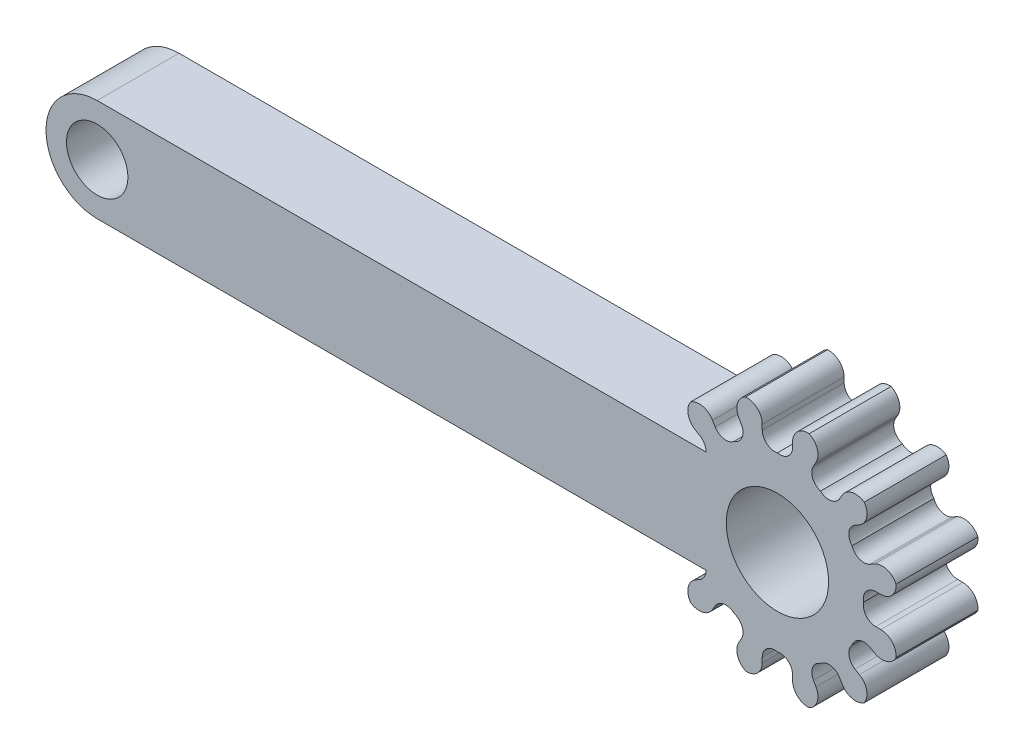
SolidWorks part; units mm, degrees
ref_plane "Front Plane" through (0, 0, 0) normal (0, 0, 1) x (1, 0, 0)
ref_plane "Top Plane" through (0, 0, 0) normal (0, 1, 0) x (1, 0, 0)
ref_plane "Right Plane" through (0, 0, 0) normal (1, 0, 0) x (0, 0, -1)
sketch "Sketch1" plane through (0, 0, 0) normal (0, 0, 1) x (1, 0, 0)
  line L0 (-18, 0) -> (15.2239, 0) construction
  line L1 (-18, 0) -> (-18, 2.5) construction
  line L2 (-18, 2.5) -> (9.7696, 2.5)
  line L3 (-18, -2.5) -> (9.7696, -2.5)
  arc A0 (-18, 2.5) -> (-18, -2.5) centre (-18, 0) ccw
  circle A1 centre (-18, 0) radius 1.5
  arc A3 (9.7696, -2.5) -> (9.7696, 2.5) centre (15.2239, 0) ccw
  point P4 (0, 0)
  dimension "D2" = 3
  dimension "D3" = 5
  dimension "D1" = 12
extrude "Boss-Extrude1" add sketch "Sketch1" along normal blind 4
sketch "Sketch2" plane through (0, 0, 4) normal (0, 0, 1) x (1, 0, 0)
  line L0 (15.2239, 0) -> (15.2239, -8.1619) construction
  line L1 (15.2239, -8.1619) -> (15.2239, 0) construction
  line L2 (15.2239, 6) -> (15.2239, -8.1619) construction
  line L3 (15.2239, 0) -> (19.4666, 4.2426) construction
  line L4 (15.2239, 0) -> (16.7769, 5.7956) construction
  line L5 (15.2239, 0) -> (17.3289, 3.646) construction
  line L6 (17.1076, 4.7464) -> (16.9838, 4.5292)
  line L7 (18.3927, 4.0045) -> (18.2664, 3.7887)
  arc A1 (16.7769, 5.7956) -> (17.1076, 4.7464) centre (16.4559, 5.1177) cw
  arc A6 (9.7696, -2.5) -> (9.7696, 2.5) centre (15.2239, 0) ccw construction
  arc A7 (16.9838, 4.5292) -> (17.3289, 3.646) centre (17.5138, 4.2273) ccw
  arc A8 (18.2664, 3.7887) -> (17.3289, 3.646) centre (17.7399, 4.0967) cw
  arc A9 (19.4666, 4.2426) -> (18.3927, 4.0045) centre (19.04, 3.6258) ccw
  arc A10 (16.7769, 5.7956) -> (19.4666, 4.2426) centre (17.517, 3.9717) cw
  dimension "D6" = 1.1
  dimension "D5" = 0.75
  dimension "D8" = 0.61
  dimension "D1" = 15
  dimension "D2" = 30
  dimension "D3" = 4.21
  dimension "D4" = 15
  dimension "D7" = 0.25
extrude "Cut-Extrude1" cut sketch "Sketch2" against normal through all
pattern_circular "CirPattern1" count 12 over 360 about axis through (15.2239, 0, 0) along (0, 0, 1) of "Cut-Extrude1"
sketch "Sketch3" plane through (0, 0, 4) normal (0, 0, 1) x (1, 0, 0)
  line L0 (9.2948, 2.5) -> (-18, 2.5) construction
  line L1 (5.9886, 2.5) -> (17.3253, 2.5)
  line L2 (5.9886, 2.5) -> (5.9886, -2.5)
  line L3 (5.9886, -2.5) -> (17.3253, -2.5)
  line L4 (17.3253, 2.5) -> (17.3253, -2.5)
  line L5 (-18, -2.5) -> (9.2948, -2.5) construction
extrude "Boss-Extrude2" add sketch "Sketch3" against normal blind 4
sketch "Sketch4" plane through (0, 0, 4) normal (0, 0, 1) x (1, 0, 0)
  line L0 (15.2239, 6) -> (15.2239, -6) construction
  circle A0 centre (15.2239, 0) radius 2.5
  point P6 (0, 0)
  point P7 (0, 0)
  dimension "D1" = 5
extrude "Cut-Extrude2" cut sketch "Sketch4" against normal through all
